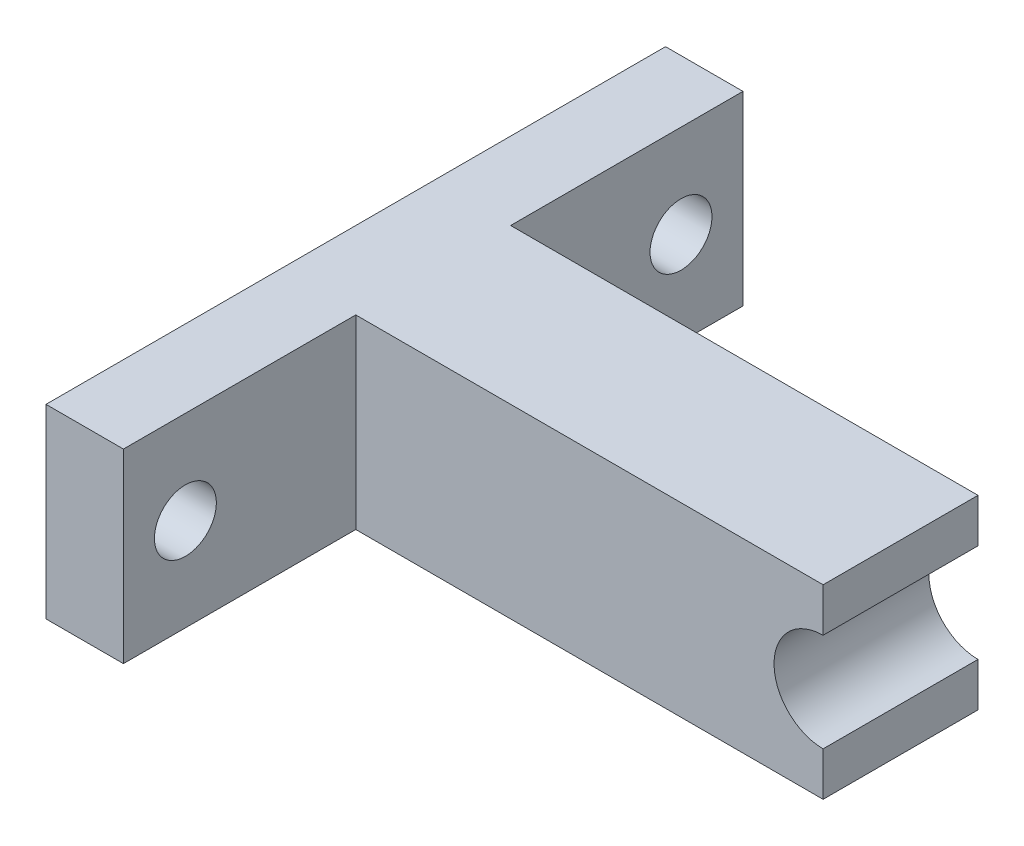
SolidWorks part; units mm, degrees
ref_plane "Front Plane" through (0, 0, 0) normal (0, 0, 1) x (1, 0, 0)
ref_plane "Top Plane" through (0, 0, 0) normal (0, 1, 0) x (1, 0, 0)
ref_plane "Right Plane" through (0, 0, 0) normal (1, 0, 0) x (0, 0, -1)
sketch "Sketch1" plane through (0, 0, 0) normal (1, 0, 0) x (0, 0, -1)
  line L0 (-20, 0) -> (20, 0) construction
  line L1 (-20, -6) -> (20, -6)
  line L2 (-20, -6) -> (-20, 6)
  line L3 (-20, 6) -> (20, 6)
  line L4 (20, -6) -> (20, 6)
  line L5 (-20, -6) -> (20, 6) construction
  line L6 (-20, 6) -> (20, -6) construction
  line L7 (0, 6) -> (0, -6) construction
  circle A0 centre (-16, 0) radius 2
  circle A1 centre (16, 0) radius 2
  point P0 (0, 0)
  dimension "D3" = 16
  dimension "D4" = 4
  dimension "D1" = 40
  dimension "D2" = 12
extrude "Boss-Extrude1" add sketch "Sketch1" along normal blind 5
sketch "Sketch2" plane through (0, 0, 0) normal (0, 1, 0) x (1, 0, 0)
  line L0 (5, 20) -> (5, -20) construction
  line L1 (35.175, -5) -> (5, -5)
  line L3 (35.175, 5) -> (5, 5)
  line L4 (5, -5) -> (5, 5)
  line L5 (35.175, -5) -> (5, 5) construction
  line L6 (35.175, 5) -> (5, -5) construction
  line L7 (0, 0) -> (20.0875, 0) construction
  line L8 (35.175, 5) -> (35.175, -5)
  point P0 (20.0875, 0)
  dimension "D1" = 30.175
  dimension "D2" = 10
extrude "Boss-Extrude2" add sketch "Sketch2" along normal mid plane 12
sketch "Sketch3" plane through (0, 0, 0) normal (0, 0, 1) x (1, 0, 0)
  line L0 (35.18, 6) -> (35.18, -6) construction
  line L1 (5, 6) -> (35.175, 6) construction
  line L2 (5, -6) -> (35.175, -6) construction
  line L3 (5, 6) -> (5, -6) construction
  circle A0 centre (35.18, 0) radius 3.175
  dimension "D1" = 6.35
  dimension "D2" = 30.18
extrude "Cut-Extrude1" cut sketch "Sketch3" against normal mid plane 34
